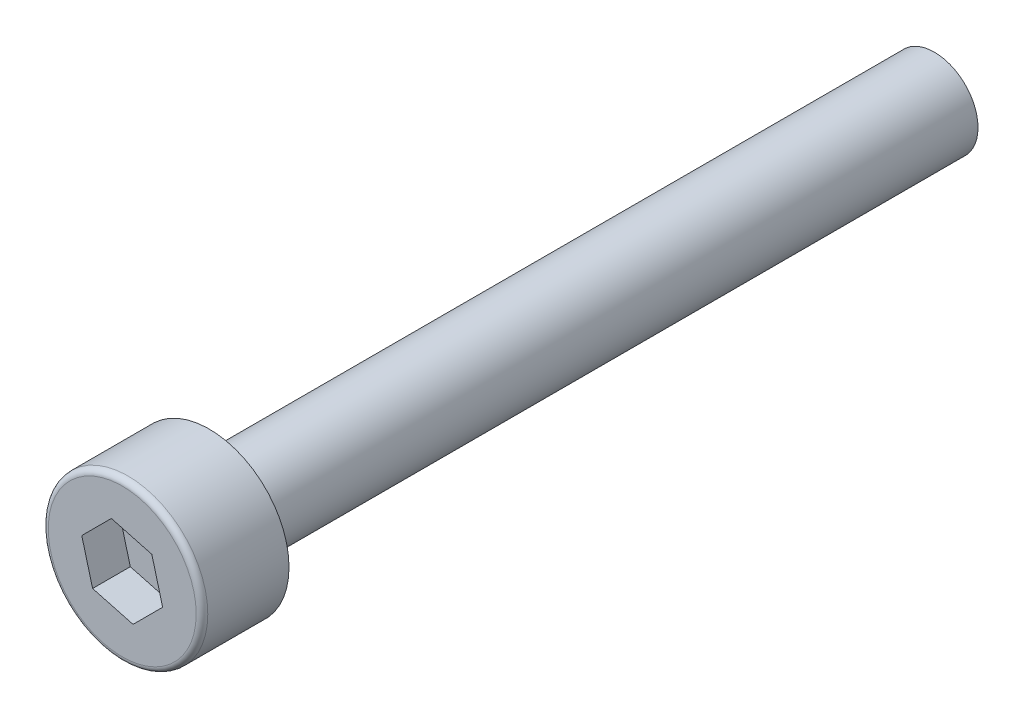
SolidWorks part; units mm, degrees
ref_plane "前视基准面" through (0, 0, 0) normal (0, 0, 1) x (1, 0, 0)
ref_plane "上视基准面" through (0, 0, 0) normal (0, 1, 0) x (1, 0, 0)
ref_plane "右视基准面" through (0, 0, 0) normal (1, 0, 0) x (0, 0, -1)
sketch "草图1" plane through (0, 0, 0) normal (0, 0, 1) x (1, 0, 0)
  circle A0 centre (0, 0) radius 2.75
  dimension "D1" = 5.5
extrude "凸台-拉伸1" add sketch "草图1" along normal blind 3
sketch "草图2" plane through (0, 0, 3) normal (0, 0, 1) x (1, 0, 0)
  line L1 (-1.0206, -1.0206) -> (0.3736, -1.3942)
  line L2 (0.3736, -1.3942) -> (1.3942, -0.3736)
  line L3 (1.3942, -0.3736) -> (1.0206, 1.0206)
  line L4 (1.0206, 1.0206) -> (-0.3736, 1.3942)
  line L5 (-0.3736, 1.3942) -> (-1.3942, 0.3736)
  line L6 (-1.3942, 0.3736) -> (-1.0206, -1.0206)
  circle A0 centre (0, 0) radius 1.25 construction
  dimension "D1" = 2.5
extrude "切除-拉伸1" cut sketch "草图2" against normal blind 1.3
sketch "草图3" plane through (0, 0, 0) normal (0, 0, -1) x (-1, 0, 0)
  circle A0 centre (0, 0) radius 1.5
  dimension "D1" = 3
extrude "凸台-拉伸2" add sketch "草图3" along normal blind 25
fillet "圆角1" radius 0.2 1 edges at (2.75, 0, 3)
